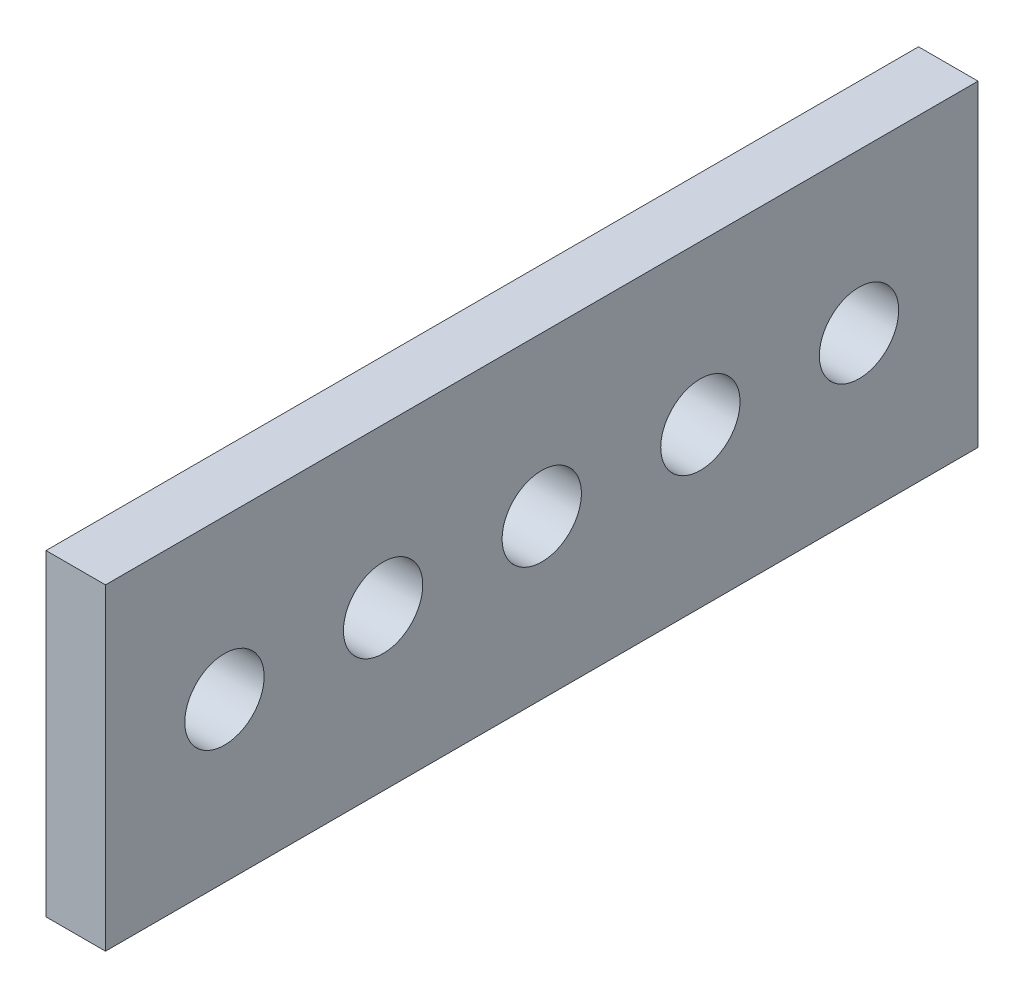
SolidWorks part; units mm, degrees
material "6061 Alloy"
ref_plane "Front Plane" through (0, 0, 0) normal (0, 0, 1) x (1, 0, 0)
ref_plane "Top Plane" through (0, 0, 0) normal (0, 1, 0) x (1, 0, 0)
ref_plane "Right Plane" through (0, 0, 0) normal (1, 0, 0) x (0, 0, -1)
sketch "Sketch1" plane through (0, 0, 0) normal (1, 0, 0) x (0, 0, -1)
  line L1 (-34.925, -12.7) -> (34.925, -12.7)
  line L2 (-34.925, -12.7) -> (-34.925, 12.7)
  line L3 (-34.925, 12.7) -> (34.925, 12.7)
  line L4 (34.925, -12.7) -> (34.925, 12.7)
  line L5 (-34.925, -12.7) -> (34.925, 12.7) construction
  line L6 (-34.925, 12.7) -> (34.925, -12.7) construction
  circle A0 centre (0, 0) radius 3.175
  circle A1 centre (-12.7, 0) radius 3.175
  circle A2 centre (-25.4, 0) radius 3.175
  circle A3 centre (12.7, 0) radius 3.175
  circle A4 centre (25.4, 0) radius 3.175
  point P0 (0, 0)
  dimension "D3" = 6.35
  dimension "D4" = 12.7
  dimension "D5" = 12.7
  dimension "D6" = 25.4
  dimension "D7" = 12.7
  dimension "D8" = 25.4
  dimension "D1" = 69.85
  dimension "D2" = 25.4
extrude "Boss-Extrude1" add sketch "Sketch1" along normal blind 4.7625
